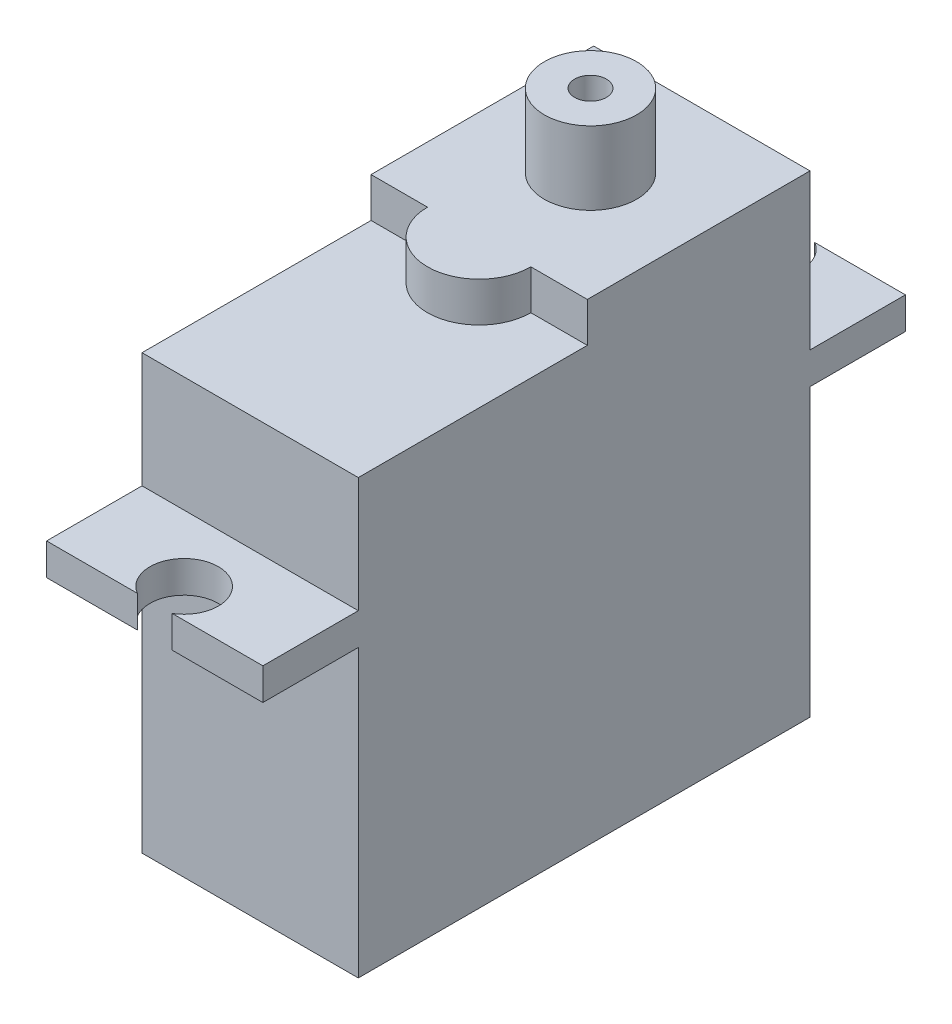
SolidWorks part; units mm, degrees
ref_plane "Front Plane" through (0, 0, 0) normal (0, 0, 1) x (1, 0, 0)
ref_plane "Top Plane" through (0, 0, 0) normal (0, 1, 0) x (1, 0, 0)
ref_plane "Right Plane" through (0, 0, 0) normal (1, 0, 0) x (0, 0, -1)
sketch "Sketch1" plane through (0, 0, 0) normal (0, 1, 0) x (1, 0, 0)
  line L1 (-6.8, -14.2) -> (6.8, -14.2)
  line L2 (-6.8, -14.2) -> (-6.8, 14.2)
  line L3 (-6.8, 14.2) -> (6.8, 14.2)
  line L4 (6.8, -14.2) -> (6.8, 14.2)
  line L5 (-6.8, -14.2) -> (6.8, 14.2) construction
  line L6 (-6.8, 14.2) -> (6.8, -14.2) construction
  point P0 (0, 0)
  dimension "D1" = 13.6
  dimension "D2" = 28.4
extrude "Boss-Extrude1" add sketch "Sketch1" along normal blind 27.25
sketch "Sketch2" plane through (0, 27.25, 0) normal (0, 1, 0) x (1, 0, 0)
  line L0 (-6.8, 14.2) -> (-6.8, -14.2) construction
  line L1 (6.8, 14.2) -> (-6.8, 14.2)
  line L2 (6.8, 14.2) -> (6.8, 0.2)
  line L3 (6.8, 0.2) -> (-6.8, 0.2)
  line L4 (-6.8, 14.2) -> (-6.8, 0.2)
  circle A0 centre (0, 0.2) radius 3.25
  line M1 (6.8, -14.2) -> (6.8, 14.2)
  line M2 (6.8, 14.2) -> (-6.8, 14.2)
  line M3 (-6.8, 14.2) -> (-6.8, -14.2)
  dimension "D2" = 6.5
  dimension "D1" = 14
extrude "Boss-Extrude2" add sketch "Sketch2" along normal blind 2.5 contours L3 A0 | L3 A0 | A0 L3 M1 M2 M3
sketch "Sketch3" plane through (0, 29.75, 0) normal (0, 1, 0) x (1, 0, 0)
  line L0 (6.8, 0.2) -> (6.8, 14.2) construction
  line L1 (6.8, 14.2) -> (-6.8, 14.2) construction
  circle A0 centre (0, 7.2) radius 2.9
  circle A1 centre (0, 7.2) radius 1
  dimension "D1" = 5.8
  dimension "D2" = 2
  dimension "D3" = 6.8
  dimension "D4" = 7
extrude "Boss-Extrude3" add sketch "Sketch3" along normal blind 4.6
ref_plane "Plane2" through (0, 20, 0) normal (0, -1, 0) x (-1, 0, 0)
sketch "Sketch5" plane through (0, 20, 0) normal (0, -1, 0) x (-1, 0, 0)
  line L0 (6.8, -14.2) -> (-6.8, -14.2) construction
  line L1 (6.8, 20.2) -> (-6.8, 20.2)
  line L2 (6.8, 20.2) -> (6.8, -20.2)
  line L3 (6.8, -20.2) -> (-6.8, -20.2)
  line L4 (-6.8, 20.2) -> (-6.8, -20.2)
  line L5 (6.8, 20.2) -> (-6.8, -20.2) construction
  line L6 (6.8, -20.2) -> (-6.8, 20.2) construction
  line L7 (6.8, 0.2) -> (6.8, -14.2) construction
  point P0 (0, 0)
  dimension "D1" = 6
  dimension "D2" = 0
extrude "Boss-Extrude5" add sketch "Sketch5" along normal blind 2
sketch "Sketch7" plane through (0, 20, 0) normal (0, 1, 0) x (1, 0, 0)
  line L0 (-6.8, 20.2) -> (6.8, 20.2) construction
  line L1 (6.8, 20.2) -> (6.8, 14.2) construction
  circle A0 centre (0, 18.35) radius 2.15
  dimension "D1" = 4.3
  dimension "D2" = 1.85
  dimension "D3" = 6.8
sketch "Sketch8" plane through (0, 20, 0) normal (0, 1, 0) x (1, 0, 0)
  line L0 (6.8, -20.2) -> (-6.8, -20.2) construction
  line L1 (-6.8, -20.2) -> (-6.8, -14.2) construction
  circle A0 centre (0, -18.35) radius 2.15
  dimension "D1" = 4.3
  dimension "D2" = 1.85
  dimension "D3" = 6.8
extrude "Cut-Extrude1" cut sketch "Sketch8" against normal up to surface (2 mm away) contours A0 up to face at (0, 18, 17.2)
extrude "Cut-Extrude2" cut sketch "Sketch7" against normal up to surface (2 mm away) contours A0 up to face at (0, 18, -17.2)
